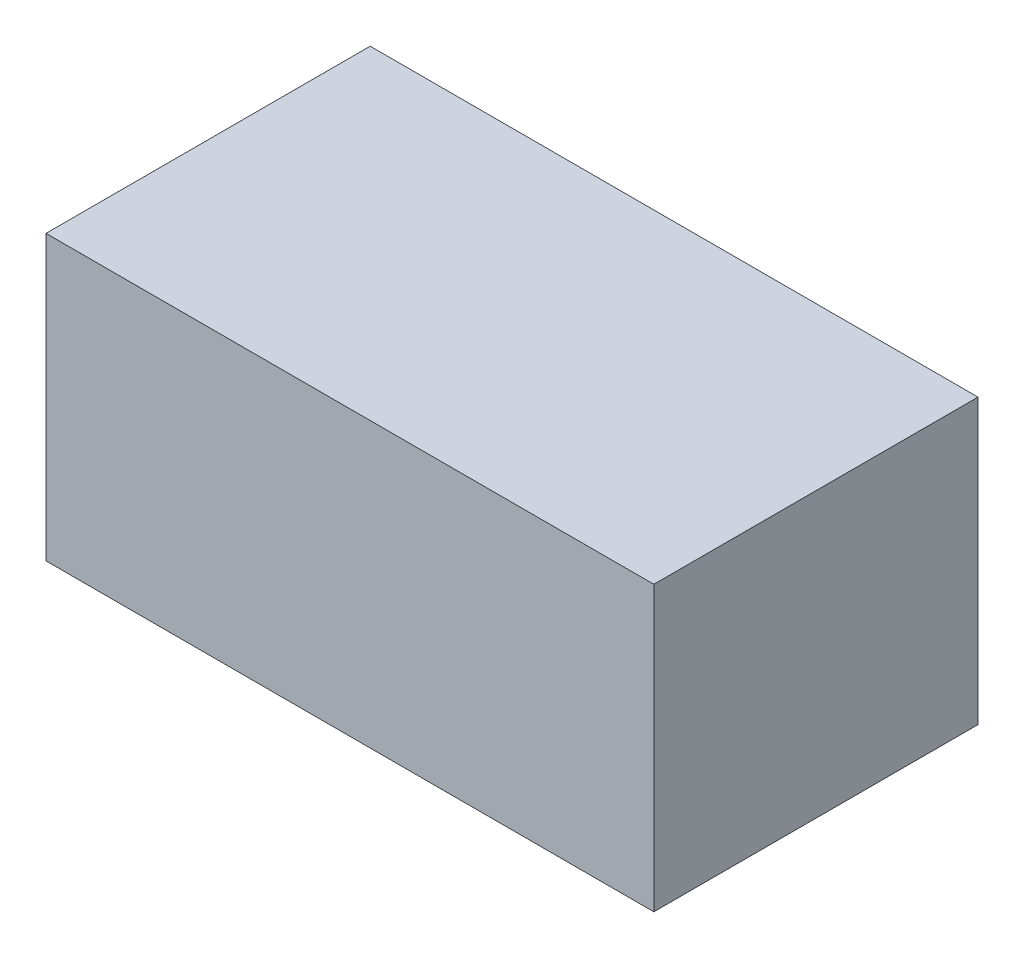
SolidWorks part; units mm, degrees
ref_plane "Front Plane" through (0, 0, 0) normal (0, 0, 1) x (1, 0, 0)
ref_plane "Top Plane" through (0, 0, 0) normal (0, 1, 0) x (1, 0, 0)
ref_plane "Right Plane" through (0, 0, 0) normal (1, 0, 0) x (0, 0, -1)
sketch "Sketch1" plane through (0, 0, 0) normal (0, 1, 0) x (1, 0, 0)
  line L1 (-2065.0334, 940.1125) -> (2506.9666, 940.1125)
  line L2 (-2065.0334, 940.1125) -> (-2065.0334, -1498.2875)
  line L3 (-2065.0334, -1498.2875) -> (2506.9666, -1498.2875)
  line L4 (2506.9666, 940.1125) -> (2506.9666, -1498.2875)
  dimension "D1" = 4572
  dimension "D2" = 2438.4
extrude "Boss-Extrude1" add sketch "Sketch1" along normal blind 2133.6
